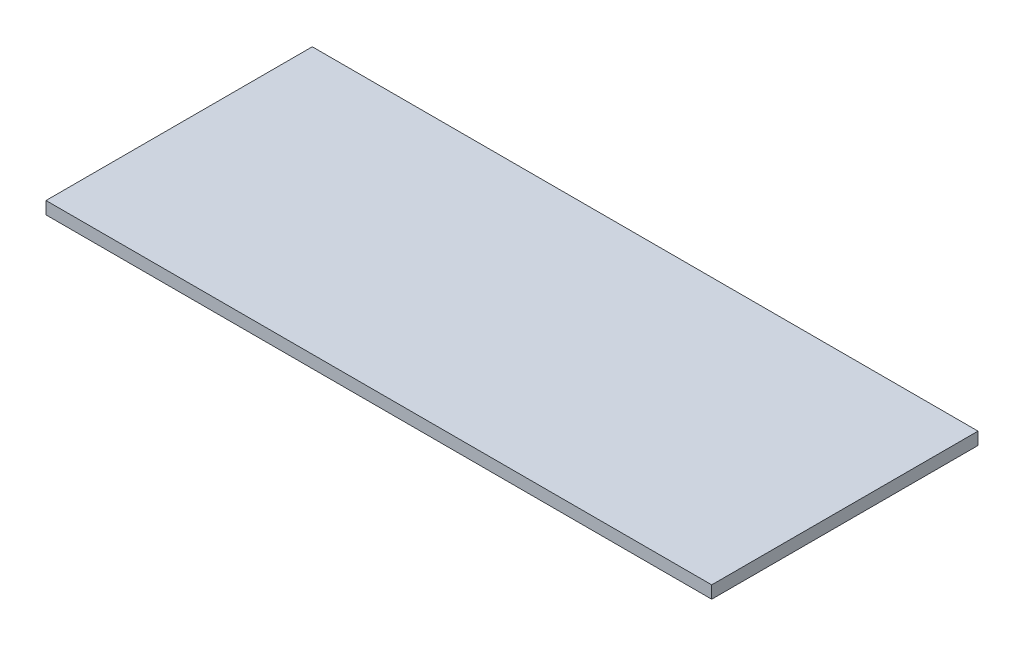
SolidWorks part; units mm, degrees
ref_plane "Front Plane" through (0, 0, 0) normal (0, 0, 1) x (1, 0, 0)
ref_plane "Top Plane" through (0, 0, 0) normal (0, 1, 0) x (1, 0, 0)
ref_plane "Right Plane" through (0, 0, 0) normal (1, 0, 0) x (0, 0, -1)
sketch "Sketch1" plane through (0, 0, 0) normal (0, 1, 0) x (1, 0, 0)
  line L1 (0, 0) -> (254, 0)
  line L2 (0, 0) -> (0, 101.6)
  line L3 (0, 101.6) -> (254, 101.6)
  line L4 (254, 0) -> (254, 101.6)
  dimension "D1" = 101.6
  dimension "D2" = 254
extrude "Boss-Extrude1" add sketch "Sketch1" along normal blind 4.7625
